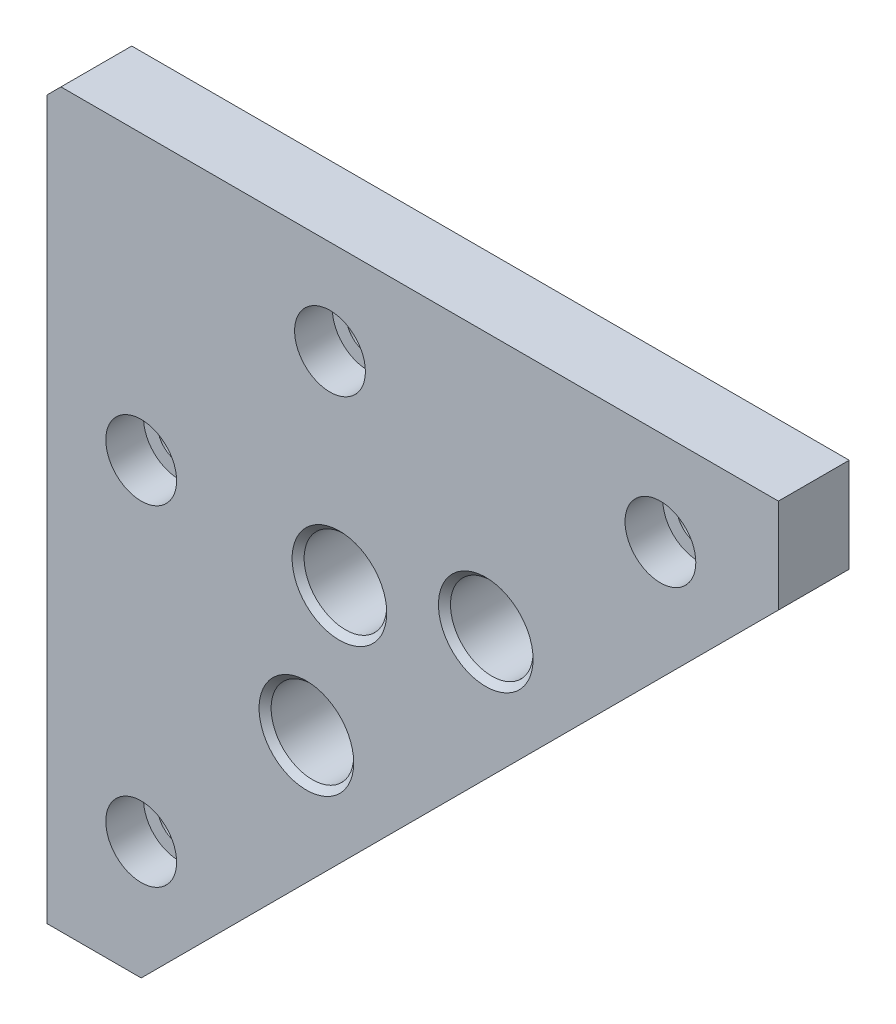
SolidWorks part; units mm, degrees
ref_plane "정면" through (0, 0, 0) normal (0, 0, 1) x (1, 0, 0)
ref_plane "윗면" through (0, 0, 0) normal (0, 1, 0) x (1, 0, 0)
ref_plane "우측면" through (0, 0, 0) normal (1, 0, 0) x (0, 0, -1)
sketch "스케치1" plane through (0, 0, 0) normal (0, 0, 1) x (1, 0, 0)
  line L0 (155, 135) -> (20, 0)
  line L1 (0, 0) -> (20, 0)
  line L2 (0, 0) -> (0, 152)
  line L3 (3, 155) -> (155, 155)
  line L4 (155, 135) -> (155, 155)
  line L5 (0, 152) -> (3, 155)
  point P2 (0, 155)
  dimension "D1" = 20
  dimension "D2" = 20
  dimension "D3" = 155
  dimension "D4" = 135
extrude "보스-돌출1" add sketch "스케치1" along normal blind 15
sketch "스케치3" plane through (0, 0, 15) normal (0, 0, 1) x (1, 0, 0)
  point P0 (62, 93)
  point P1 (55, 62)
  point P2 (93, 100)
  dimension "D1" = 55
  dimension "D2" = 62
  dimension "D3" = 7
  dimension "D4" = 31
  dimension "D5" = 7
  dimension "D6" = 31
hole_wizard "M20 나사 구멍1" positions "스케치3" profile "스케치4" tap size "M20" standard "ISO" end condition through all
sketch "스케치4" plane through (62, 93, 15) normal (1, 0, 0) x (0, -1, 0)
  line L0 (0, 0) -> (0, 15)
  line L1 (0, 15) -> (8.75, 15)
  line L2 (8.75, 15) -> (8.75, 1.275)
  line L3 (8.75, 1.275) -> (10.025, 0)
  line L5 (10.025, 0) -> (0, 0)
  line L6 (-8.75, 1.275) -> (-10.025, 0) construction
  line L11 (0, -6.35) -> (0, 107.95) construction
  dimension "관통 탭 드릴 지름" = 17.5
  dimension "관통 탭 드릴 깊이" = 15
  dimension "표면 카운터싱크 지름" = 20.05
  dimension "표면 카운터싱크 각도" = 90
cosmetic thread "구멍 나사산1" parameters "D2"=20
cosmetic thread "구멍 나사산2" parameters "D2"=20
cosmetic thread "구멍 나사산3" parameters "D2"=20
sketch "스케치5" plane through (0, 0, 15) normal (0, 0, 1) x (1, 0, 0)
  line L0 (0, 152) -> (0, 0) construction
  circle A0 centre (60, 135) radius 4.5
  circle A1 centre (20, 95) radius 4.5
  circle A2 centre (130, 135) radius 4.5
  circle A3 centre (20, 25) radius 4.5
  point P8 (0, 0)
  dimension "D7" = 9
  dimension "D1" = 20
  dimension "D2" = 40
  dimension "D3" = 70
  dimension "D4" = 25
  dimension "D5" = 70
  dimension "D6" = 40
extrude "컷-돌출1" cut sketch "스케치5" against normal through all
sketch "스케치6" plane through (0, 0, 15) normal (0, 0, 1) x (1, 0, 0)
  circle A0 centre (20, 95) radius 7.5
  circle A1 centre (20, 25) radius 7.5
  circle A2 centre (60, 135) radius 7.5
  circle A3 centre (130, 135) radius 7.5
  dimension "D1" = 15
extrude "컷-돌출2" cut sketch "스케치6" against normal blind 8
